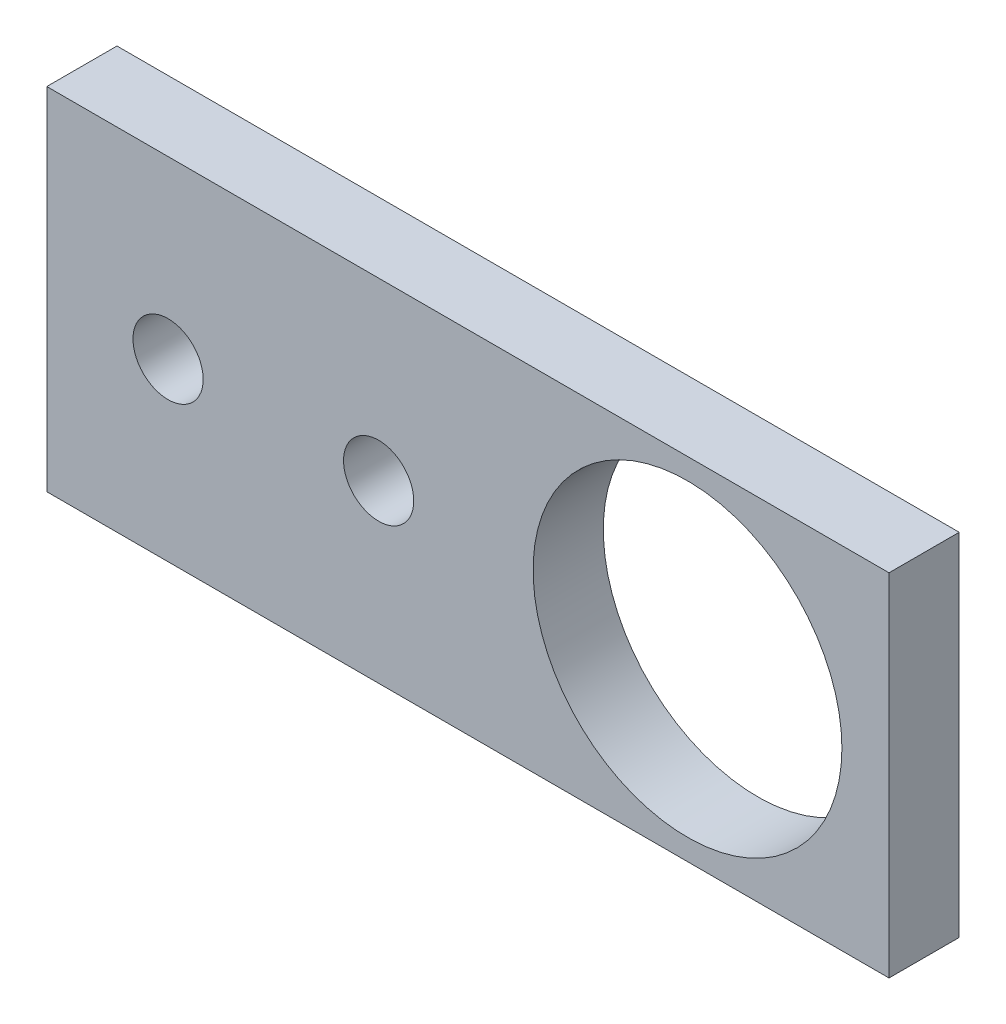
SolidWorks part; units mm, degrees
ref_plane "Front Plane" through (0, 0, 0) normal (0, 0, 1) x (1, 0, 0)
ref_plane "Top Plane" through (0, 0, 0) normal (0, 1, 0) x (1, 0, 0)
ref_plane "Right Plane" through (0, 0, 0) normal (1, 0, 0) x (0, 0, -1)
sketch "Sketch1" plane through (0, 0, 0) normal (0, 0, 1) x (1, 0, 0)
  line L1 (30, 12.5) -> (-30, 12.5)
  line L2 (30, 12.5) -> (30, -12.5)
  line L3 (30, -12.5) -> (-30, -12.5)
  line L4 (-30, 12.5) -> (-30, -12.5)
  line L5 (30, 12.5) -> (-30, -12.5) construction
  line L6 (30, -12.5) -> (-30, 12.5) construction
  circle A0 centre (-21.3599, 0) radius 2.5
  circle A1 centre (15.6442, 0) radius 11
  circle A2 centre (-6.3599, 0) radius 2.5
  point P0 (0, 0)
  dimension "D3" = 5
  dimension "D4" = 22
  dimension "D5" = 5
  dimension "D6" = 15
  dimension "D1" = 60
  dimension "D2" = 25
extrude "Boss-Extrude2" add sketch "Sketch1" along normal blind 5
